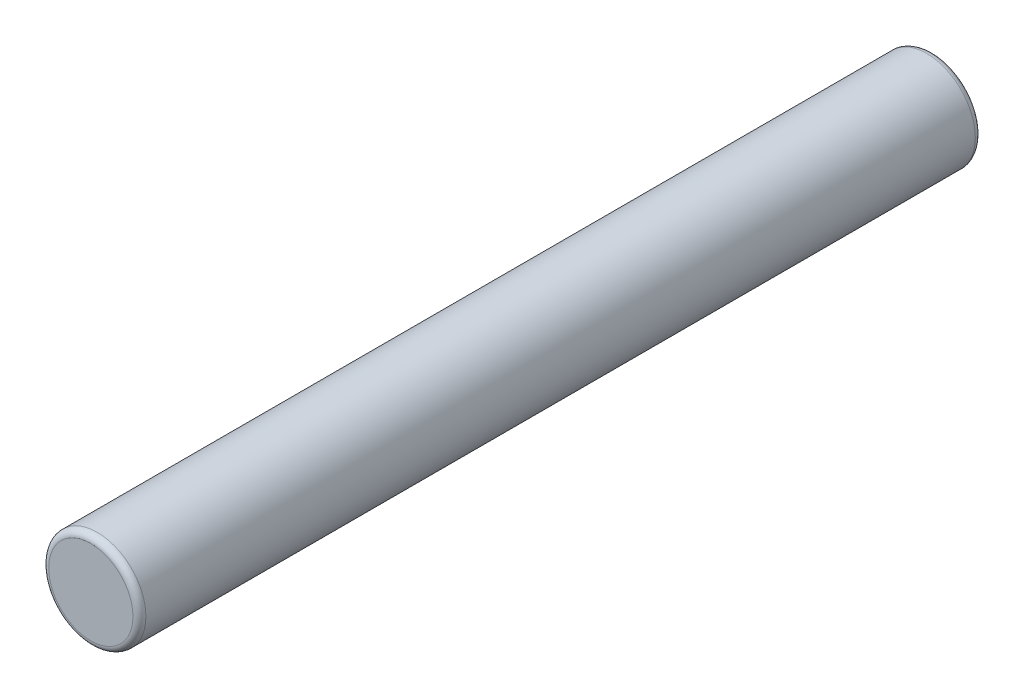
SolidWorks part; units mm, degrees
ref_plane "Płaszczyzna przednia" through (0, 0, 0) normal (0, 0, 1) x (1, 0, 0)
ref_plane "Płaszczyzna górna" through (0, 0, 0) normal (0, 1, 0) x (1, 0, 0)
ref_plane "Płaszczyzna prawa" through (0, 0, 0) normal (1, 0, 0) x (0, 0, -1)
sketch "Sketch1" plane through (0, 0, 0) normal (0, 0, 1) x (1, 0, 0)
  circle A0 centre (0, 0) radius 1.5
  dimension "D1" = 3
extrude "Boss-Extrude1" add sketch "Sketch1" along normal blind 26
fillet "Fillet1" radius 0.2 2 edges at (1.5, 0, 26) (1.5, 0, 0)
